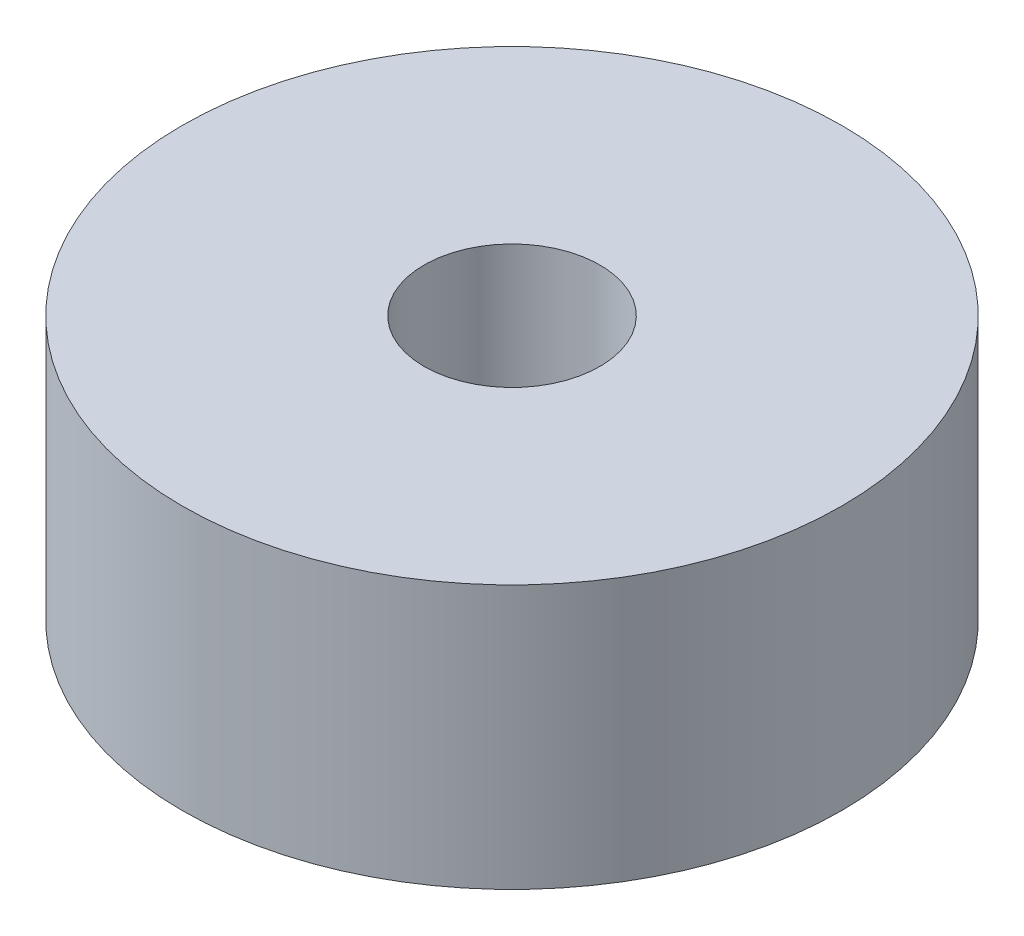
SolidWorks part; units mm, degrees
ref_plane "前视基准面" through (0, 0, 0) normal (0, 0, 1) x (1, 0, 0)
ref_plane "上视基准面" through (0, 0, 0) normal (0, 1, 0) x (1, 0, 0)
ref_plane "右视基准面" through (0, 0, 0) normal (1, 0, 0) x (0, 0, -1)
sketch "Sketch1" plane through (0, 0, 0) normal (0, 1, 0) x (1, 0, 0)
  circle A0 centre (0, 0) radius 15
  circle A1 centre (0, 0) radius 4
  dimension "D1" = 30
  dimension "D2" = 8
extrude "Boss-Extrude1" add sketch "Sketch1" along normal blind 12
